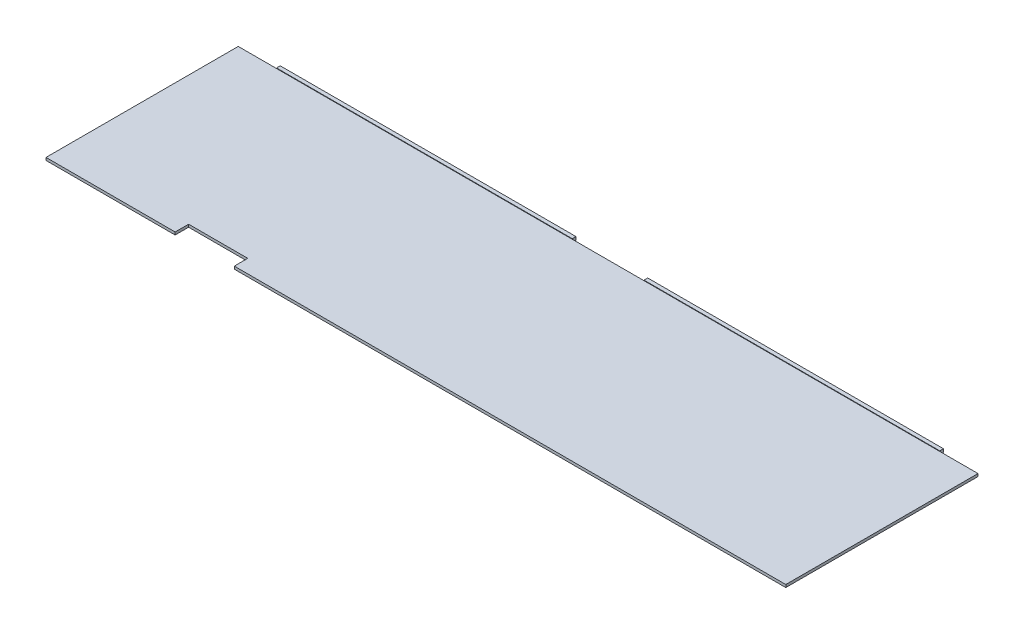
SolidWorks part; units mm, degrees
material "6061-T6 (SS)"
ref_plane "X-Y Datum" through (0, 0, 0) normal (0, 0, 1) x (1, 0, 0)
ref_plane "X-Z Datum" through (0, 0, 0) normal (0, 1, 0) x (1, 0, 0)
ref_plane "Y-Z Datum" through (0, 0, 0) normal (1, 0, 0) x (0, 0, -1)
sketch "Sketch1" plane through (0, 0, 0) normal (0, 1, 0) x (1, 0, 0)
  line L1 (-317.6778, 82.55) -> (317.6778, 82.55)
  line L2 (-317.6778, 82.55) -> (-317.6778, -82.55)
  line L3 (-317.6778, -82.55) -> (317.6778, -82.55)
  line L4 (317.6778, 82.55) -> (317.6778, -82.55)
  line L5 (-317.6778, 82.55) -> (317.6778, -82.55) construction
  line L6 (-317.6778, -82.55) -> (317.6778, 82.55) construction
  point P0 (0, 0)
  dimension "D1" = 635.3556
  dimension "D2" = 165.1
extrude "Boss-Extrude1" add sketch "Sketch1" along normal mid plane 2.286
sketch "Sketch2" plane through (0, 0, -82.55) normal (0, 0, -1) x (-1, 0, 0)
  line L20 (-317.6778, -1.143) -> (317.6778, -1.143) construction
  line L21 (-284.8229, -1.143) -> (-30.8229, -1.143)
  line L22 (30.8229, -1.143) -> (284.8229, -1.143)
  line L40 (30.8229, -1.143) -> (30.8229, 1.5875)
  line L41 (30.8229, 1.5875) -> (284.8229, 1.5875)
  line L42 (284.8229, 1.5875) -> (284.8229, -1.143)
  line L56 (-284.8229, -1.143) -> (-284.8229, 1.5875)
  line L57 (-284.8229, 1.5875) -> (-30.8229, 1.5875)
  line L58 (-30.8229, 1.5875) -> (-30.8229, -1.143)
extrude "Boss-Extrude2" add sketch "Sketch2" along normal blind 3.175
sketch "Sketch3" plane through (0, -1.143, 0) normal (0, -1, 0) x (1, 0, 0)
  line L0 (-311.5097, 70.9775) -> (-206.7709, 70.9775) construction
  line L1 (-206.7709, 93.745) -> (-155.9709, 93.745)
  line L2 (-206.7709, 93.745) -> (-206.7709, 70.9775)
  line L4 (-155.9709, 93.745) -> (-155.9709, 70.9775)
  line L7 (-311.5097, 70.9775) -> (-155.9709, 70.9775)
  line L8 (-155.9709, 70.9775) -> (311.5097, 70.9775) construction
  line L9 (-155.9709, 70.9775) -> (-155.9709, 82.979) construction
  line M2 (317.6778, 82.55) -> (-317.6778, 82.55)
extrude "Cut-Extrude1" cut sketch "Sketch3" against normal through all contours L4 L1 L2 M2 | L2 L7 L4 M2
